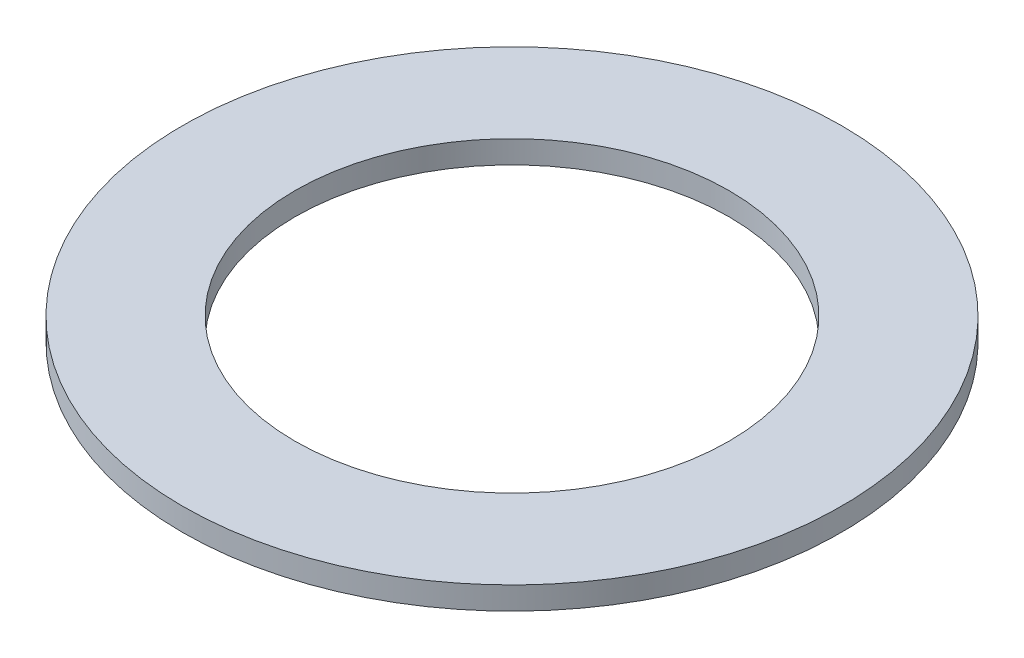
SolidWorks part; units mm, degrees
material "6061 Alloy"
ref_plane "Front Plane" through (0, 0, 0) normal (0, 0, 1) x (1, 0, 0)
ref_plane "Top Plane" through (0, 0, 0) normal (0, 1, 0) x (1, 0, 0)
ref_plane "Right Plane" through (0, 0, 0) normal (1, 0, 0) x (0, 0, -1)
sketch "Sketch1" plane through (0, 0, 0) normal (0, 1, 0) x (1, 0, 0)
  circle A0 centre (0, 0) radius 9.55
  circle A1 centre (0, 0) radius 14.5
  dimension "D1" = 19.1
  dimension "D2" = 29
extrude "Boss-Extrude1" add sketch "Sketch1" along normal blind 1
